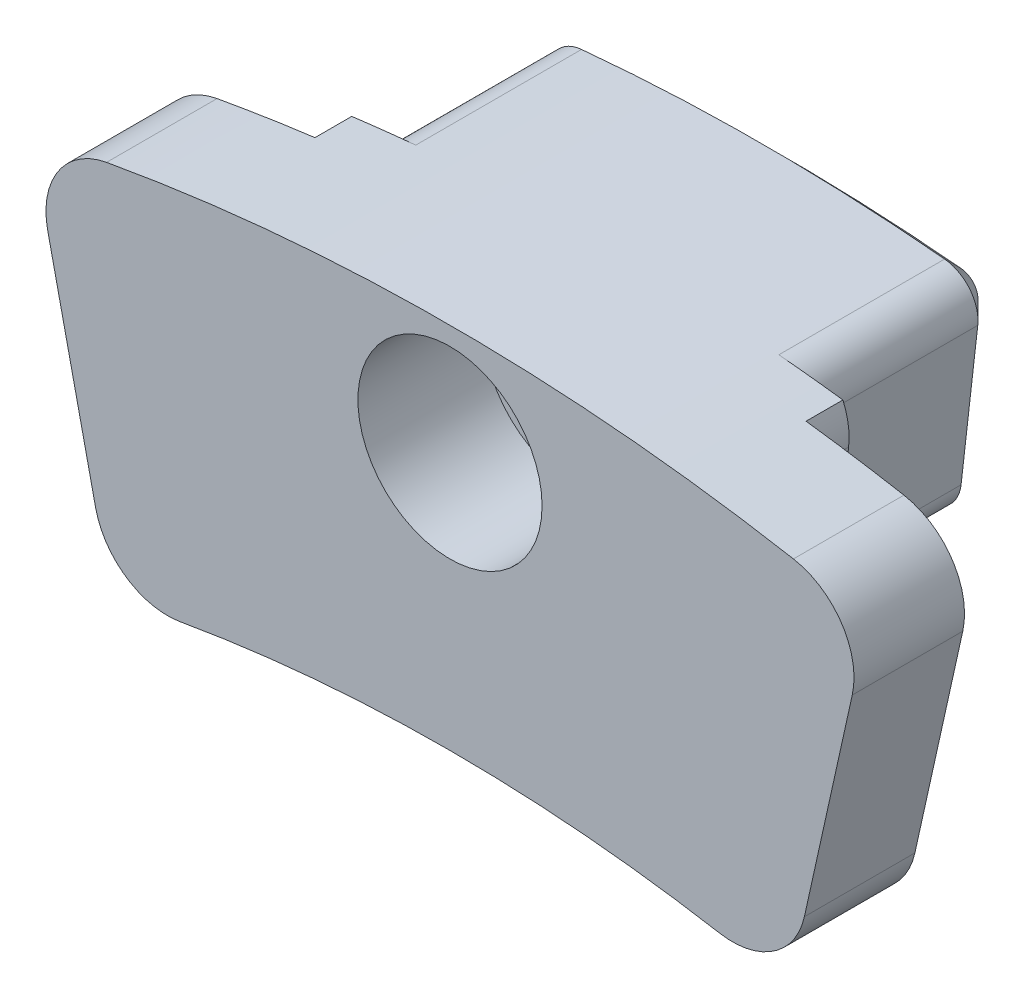
SolidWorks part; units mm, degrees
material "45#"
ref_plane "前视基准面" through (0, 0, 0) normal (0, 0, 1) x (1, 0, 0)
ref_plane "上视基准面" through (0, 0, 0) normal (0, 1, 0) x (1, 0, 0)
ref_plane "右视基准面" through (0, 0, 0) normal (1, 0, 0) x (0, 0, -1)
sketch "草图1" plane through (0, 0, 0) normal (0, 0, 1) x (1, 0, 0)
  line L2 (0, 46.5) -> (0, 52.5) construction
  line L5 (-5.2639, 46.2011) -> (-5.9432, 52.1625)
  line L6 (5.2639, 46.2011) -> (5.9432, 52.1625)
  line L7 (0, 0) -> (5.2639, 46.2011) construction
  line L8 (0, 0) -> (0, 46.5) construction
  line L9 (0, 0) -> (-5.2639, 46.2011) construction
  arc A7 (5.2639, 46.2011) -> (-5.2639, 46.2011) centre (0, 0) ccw
  arc A8 (5.9432, 52.1625) -> (-5.9432, 52.1625) centre (0, 0) ccw
  arc A9 (-5.9432, 52.1625) -> (5.9432, 52.1625) centre (0, 0) ccw construction
  arc A10 (-5.2639, 46.2011) -> (5.2639, 46.2011) centre (0, 0) ccw construction
  dimension "D1" = 13
  dimension "D2" = 93
  dimension "D3" = 105
extrude "凸台-拉伸1" add sketch "草图1" along normal blind 6
fillet "圆角1" radius 1 4 edges at (-5.2639, 46.2011, 3) (5.2639, 46.2011, 3) (5.9432, 52.1625, 3) (-5.9432, 52.1625, 3)
sketch "草图2" plane through (0, 0, 6) normal (0, 0, 1) x (1, 0, 0)
  line L0 (0, 42.5) -> (0, 46.5) construction
  line L1 (-9.1987, 41.4926) -> (-11.3631, 51.2555)
  line L2 (9.1987, 41.4926) -> (11.3631, 51.2555)
  line L3 (0, 0) -> (9.1987, 41.4926) construction
  line L4 (0, 0) -> (0, 42.5) construction
  line L5 (0, 0) -> (-9.1987, 41.4926) construction
  arc A0 (4.2901, 46.3017) -> (-4.2901, 46.3017) centre (0, 0) ccw construction
  arc A1 (9.1987, 41.4926) -> (-9.1987, 41.4926) centre (0, 0) ccw
  arc A2 (11.3631, 51.2555) -> (-11.3631, 51.2555) centre (0, 0) ccw
  arc A3 (4.9292, 52.2681) -> (-4.9292, 52.2681) centre (0, 0) ccw construction
  arc A4 (-11.3631, 51.2555) -> (11.3631, 51.2555) centre (0, 0) ccw construction
  arc A5 (-9.1987, 41.4926) -> (9.1987, 41.4926) centre (0, 0) ccw construction
  dimension "D1" = 85
  dimension "D2" = 25
extrude "凸台-拉伸2" add sketch "草图2" along normal blind 3
fillet "圆角2" radius 2 4 edges at (9.1987, 41.4926, 7.5) (11.3631, 51.2555, 7.5) (-9.1987, 41.4926, 7.5) (-11.3631, 51.2555, 7.5)
sketch "草图3" plane through (0, 0, 9) normal (0, 0, 1) x (1, 0, 0)
  line L0 (0, 46.5) -> (0, 52.5) construction
  line L2 (-5.8289, 51.1593) -> (-5.376, 47.1842)
  line L3 (5.376, 47.1842) -> (5.8289, 51.1593)
  line L4 (-5.8289, 51.1593) -> (-5.376, 47.1842) construction
  line L5 (5.376, 47.1842) -> (5.8289, 51.1593) construction
  arc A6 (4.2901, 46.3017) -> (-4.2901, 46.3017) centre (0, 0) ccw
  arc A7 (-5.376, 47.1842) -> (-4.2901, 46.3017) centre (-4.3824, 47.2974) ccw
  arc A8 (-4.9292, 52.2681) -> (-5.8289, 51.1593) centre (-4.8353, 51.2725) ccw
  arc A9 (4.9292, 52.2681) -> (-4.9292, 52.2681) centre (0, 0) ccw
  arc A10 (5.8289, 51.1593) -> (4.9292, 52.2681) centre (4.8353, 51.2725) ccw
  arc A11 (4.2901, 46.3017) -> (5.376, 47.1842) centre (4.3824, 47.2974) ccw
  arc A12 (4.2901, 46.3017) -> (-4.2901, 46.3017) centre (0, 0) ccw construction
  arc A13 (-5.376, 47.1842) -> (-4.2901, 46.3017) centre (-4.3824, 47.2974) ccw construction
  arc A14 (-4.9292, 52.2681) -> (-5.8289, 51.1593) centre (-4.8353, 51.2725) ccw construction
  arc A15 (4.9292, 52.2681) -> (-4.9292, 52.2681) centre (0, 0) ccw construction
  arc A16 (5.8289, 51.1593) -> (4.9292, 52.2681) centre (4.8353, 51.2725) ccw construction
  arc A17 (4.2901, 46.3017) -> (5.376, 47.1842) centre (4.3824, 47.2974) ccw construction
  dimension "D1" = 0
hole_wizard "打孔尺寸(%根据)内六角圆柱头螺钉的类型1" positions "草图4" profile "草图5" counterbore size "M3" standard "GB" end condition through all
sketch "草图4" plane through (0, 0, 9) normal (0, 0, 1) x (1, 0, 0)
  line L1 (0, 46.5) -> (0, 52.5) construction
  point P0 (0, 49.5)
sketch "草图5" plane through (0, 49.5, 9) normal (1, 0, 0) x (0, -1, 0)
  line L0 (0, 0) -> (0, 9)
  line L1 (0, 9) -> (1.7, 9)
  line L3 (1.7, 9) -> (1.7, 3.4)
  line L4 (1.7, 3.4) -> (2.5, 3.4)
  line L5 (2.5, 3.4) -> (2.5, 0)
  line L7 (2.5, 0) -> (0, 0)
  line L11 (0, -6.35) -> (0, 107.95) construction
  dimension "通孔孔直径" = 3.4
  dimension "通孔孔深度" = 9
  dimension "柱形沉头孔直径" = 5
  dimension "柱形沉头孔深度" = 3.4
sketch "草图6" plane through (0, 0, 6) normal (0, 0, -1) x (-1, 0, 0)
  line L11 (-5.376, 47.1842) -> (-5.8289, 51.1593) construction
  line L12 (5.8289, 51.1593) -> (5.376, 47.1842) construction
  line L13 (-6.8224, 51.0461) -> (-6.3695, 47.071)
  line L14 (6.3695, 47.071) -> (6.8224, 51.0461)
  line L15 (-6.8224, 51.0461) -> (-6.3695, 47.071)
  line L16 (6.3695, 47.071) -> (6.8224, 51.0461)
  line L17 (-5.376, 47.1842) -> (-5.8289, 51.1593)
  line L18 (5.8289, 51.1593) -> (5.376, 47.1842)
  arc A33 (-4.9292, 52.2681) -> (-5.8289, 51.1593) centre (-4.8353, 51.2725) ccw construction
  arc A34 (-5.376, 47.1842) -> (-4.2901, 46.3017) centre (-4.3824, 47.2974) ccw construction
  arc A35 (4.2901, 46.3017) -> (-4.2901, 46.3017) centre (0, 0) ccw construction
  arc A36 (5.8289, 51.1593) -> (4.9292, 52.2681) centre (4.8353, 51.2725) ccw construction
  arc A37 (4.2901, 46.3017) -> (5.376, 47.1842) centre (4.3824, 47.2974) ccw construction
  arc A38 (-5.0231, 53.2637) -> (-6.8224, 51.0461) centre (-4.8353, 51.2725) ccw
  arc A39 (-6.3695, 47.071) -> (-4.1979, 45.3059) centre (-4.3824, 47.2974) ccw
  arc A40 (6.8224, 51.0461) -> (5.0231, 53.2637) centre (4.8353, 51.2725) ccw
  arc A41 (4.1979, 45.3059) -> (6.3695, 47.071) centre (4.3824, 47.2974) ccw
  arc A42 (4.1979, 45.3059) -> (-4.1979, 45.3059) centre (0, 0) ccw
  arc A43 (-6.6673, 52.0749) -> (-6.8224, 51.0461) centre (-4.8353, 51.2725) ccw
  arc A44 (-6.3695, 47.071) -> (-4.1979, 45.3059) centre (-4.3824, 47.2974) ccw
  arc A45 (6.8224, 51.0461) -> (6.6673, 52.0749) centre (4.8353, 51.2725) ccw
  arc A46 (4.1979, 45.3059) -> (6.3695, 47.071) centre (4.3824, 47.2974) ccw
  arc A47 (4.1979, 45.3059) -> (-4.1979, 45.3059) centre (0, 0) ccw
  arc A48 (-4.9292, 52.2681) -> (-5.8289, 51.1593) centre (-4.8353, 51.2725) ccw
  arc A49 (-5.376, 47.1842) -> (-4.2901, 46.3017) centre (-4.3824, 47.2974) ccw
  arc A50 (4.2901, 46.3017) -> (-4.2901, 46.3017) centre (0, 0) ccw
  arc A51 (5.8289, 51.1593) -> (4.9292, 52.2681) centre (4.8353, 51.2725) ccw
  arc A52 (4.2901, 46.3017) -> (5.376, 47.1842) centre (4.3824, 47.2974) ccw
  arc A53 (9.3242, 51.6654) -> (4.9292, 52.2681) centre (0, 0) ccw construction
  arc A54 (-4.9292, 52.2681) -> (-9.3242, 51.6654) centre (0, 0) ccw construction
  arc A55 (6.6673, 52.0749) -> (4.9292, 52.2681) centre (0, 0) ccw
  arc A56 (-4.9292, 52.2681) -> (-6.6673, 52.0749) centre (0, 0) ccw
  arc A57 (9.3242, 51.6654) -> (6.6673, 52.0749) centre (0, 0) ccw construction
  arc A58 (6.6673, 52.0749) -> (5.0231, 53.2637) centre (4.8353, 51.2725) ccw construction
  arc A59 (-5.0231, 53.2637) -> (-6.6673, 52.0749) centre (-4.8353, 51.2725) ccw construction
  arc A60 (-6.6673, 52.0749) -> (-9.3242, 51.6654) centre (0, 0) ccw construction
  dimension "D1" = 1
extrude "凸台-拉伸3" add sketch "草图6" along normal blind 1
chamfer "倒角1" distance 0.5 angle 45 8 edges at (0, 52.5, 0) (-5.6118, 51.9026, 0) (5.6118, 51.9026, 0) (-5.6024, 49.1718, 0) (5.6024, 49.1718, 0) (-5.0131, 46.5214, 0) (5.0131, 46.5214, 0) (0, 46.5, 0)
